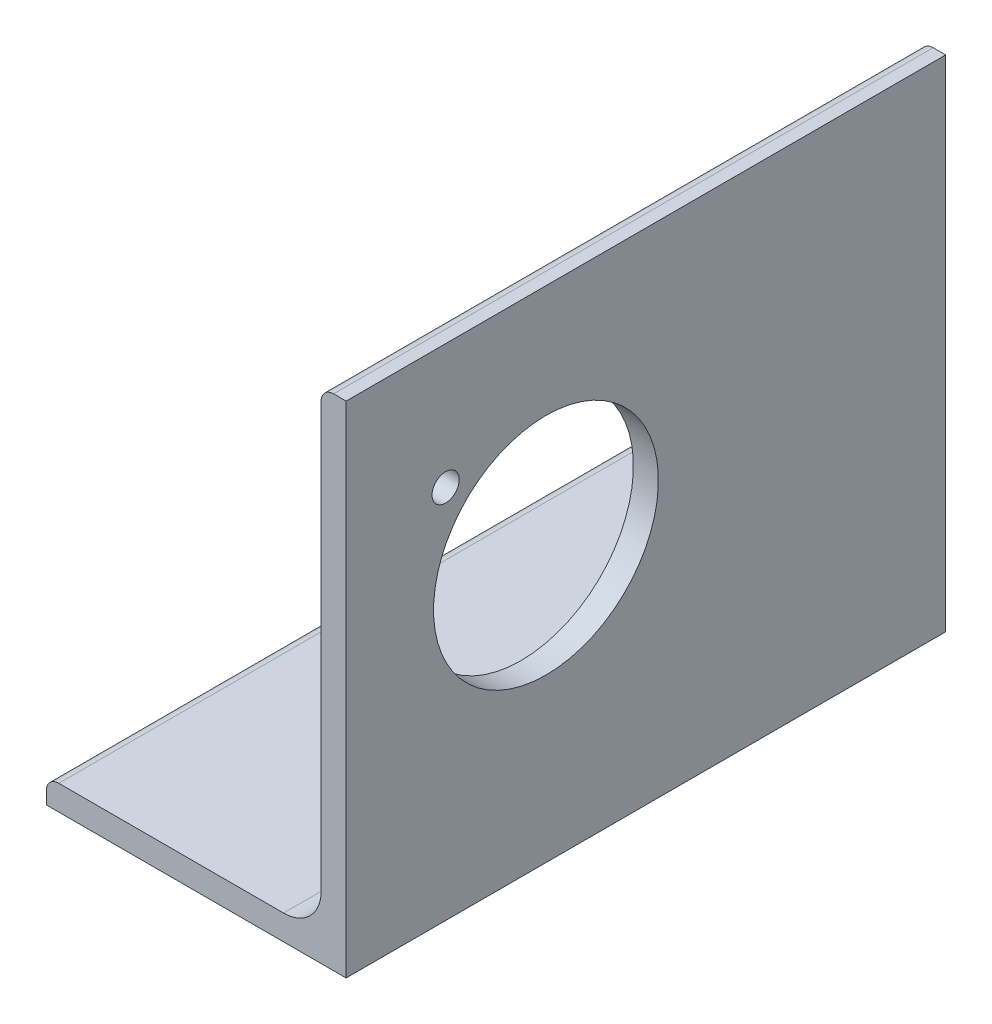
SolidWorks part; units mm, degrees
ref_plane "Front Plane" through (0, 0, 0) normal (0, 0, 1) x (1, 0, 0)
ref_plane "Top Plane" through (0, 0, 0) normal (0, 1, 0) x (1, 0, 0)
ref_plane "Right Plane" through (0, 0, 0) normal (1, 0, 0) x (0, 0, -1)
sketch "Sketch0" plane through (0, 0, 0) normal (0, 0, 1) x (1, 0, 0)
  line L0 (-19.05, -31.75) -> (19.05, -31.75)
  line L1 (19.05, -31.75) -> (19.05, 31.75)
  line L2 (19.05, 0) -> (0, 0) construction
  line L3 (0, 0) -> (0, -31.75) construction
  line L4 (15.875, -23.7998) -> (15.875, 31.75) construction
  line L5 (11.0998, -28.575) -> (-19.05, -28.575) construction
  arc A0 (15.875, -23.7998) -> (11.0998, -28.575) centre (11.0998, -23.7998) cw
  point P3 (14.4764, -27.1764)
  dimension "Inside Corner Radius" = 4.7752
  dimension "Outside Height" = 63.5
  dimension "Inside Height" = 60.325
  dimension "Inside Width" = 34.925
  dimension "Wall Thickness" = 3.175
  dimension "D1" = 3.175
  dimension "Outside Width" = 38.1
sketch "Sketch1" plane through (0, 0, 0) normal (1, 0, 0) x (0, 0, -1)
  line L0 (38.1, 0) -> (-38.1, 0)
  point P4 (0, 0)
  dimension "Length" = 76.2
sketch "Sketch2" plane through (0, 0, 0) normal (0, 0, 1) x (1, 0, 0)
  line L0 (-19.05, -31.75) -> (19.05, -31.75)
  line L1 (19.05, -31.75) -> (19.05, 31.75)
  line L2 (19.05, 31.75) -> (15.875, 31.75) construction
  line L3 (15.875, 30.1625) -> (15.875, -23.7998)
  line L4 (11.0998, -28.575) -> (-17.4625, -28.575)
  line L5 (-19.05, -31.75) -> (-19.05, -28.575) construction
  line L6 (17.4625, 31.75) -> (19.05, 31.75)
  line L7 (-19.05, -30.1625) -> (-19.05, -31.75)
  line L8 (19.05, 0) -> (0, 0) construction
  line L9 (0, 0) -> (0, -31.75) construction
  arc A0 (15.875, 30.1625) -> (17.4625, 31.75) centre (17.4625, 30.1625) cw
  arc A1 (-19.05, -30.1625) -> (-17.4625, -28.575) centre (-17.4625, -30.1625) cw
  arc A2 (15.875, -23.7998) -> (11.0998, -28.575) centre (11.0998, -23.7998) cw
  dimension "Inside Radius" = 4.7752
  dimension "Height" = 63.5
  dimension "Width" = 38.1
  dimension "Thickness" = 3.175
extrude "Boss-Extrude1" add sketch "Sketch2" along normal mid plane 76.2
sketch "Break Locations" plane through (0, 0, 0) normal (1, 0, 0) x (0, 0, -1)
  line L0 (26.67, 0) -> (-26.67, 0)
  line L1 (-38.1, -31.75) -> (-38.1, 31.75) construction
  line L2 (38.1, -31.75) -> (38.1, 31.75) construction
  point P0 (15.875, 0)
  point P1 (-15.875, 0)
  point P10 (0, 0)
  point P11 (-26.67, 0)
  point P13 (26.67, 0)
  dimension "D1" = 53.975
  dimension "D2" = 53.975
  dimension "D3" = 64.77
sketch "Sketch3" plane through (15.875, 0, 0) normal (-1, 0, 0) x (0, 0, 1)
  line L0 (12.7, 3.1798) -> (25.452, 15.9317) construction
  line L1 (12.7, 3.1798) -> (38.1, 3.1813) construction
  line L2 (38.1, 30.1625) -> (38.1, -23.7998) construction
  circle A0 centre (12.7, 3.1798) radius 14.2875
  circle A1 centre (25.452, 15.9317) radius 1.7272
  dimension "D1" = 25.4
extrude "Cut-Extrude1" cut sketch "Sketch3" against normal through all
sketch "Sketch9" plane through (0, -31.75, 0) normal (0, -1, 0) x (1, 0, 0)
  line L0 (19.05, -12.7) -> (0, -12.7) construction
  line L2 (0, -12.7) -> (0, 0) construction
  line L3 (0, -12.7) -> (0, -25.4) construction
  circle A0 centre (0, 0) radius 2.4892
  circle A1 centre (0, -25.4) radius 2.4892
  point P2 (0, 0)
  dimension "D1" = 19.05
  dimension "D2" = 25.4
  dimension "D3" = 25.4
extrude "Cut-Extrude2" cut sketch "Sketch9" against normal through all
equation "\"D1@Break Locations\" = .85 * \"Height@Sketch2\""
equation "\"D2@Break Locations\"=\"D1@Break Locations\""
equation "\"Thickness@Sketch2\"=\"wall thickness@sketch0\""
equation "\"Height@Sketch2\"=\"outside height@sketch0\""
equation "\"Width@Sketch2\"=\"outside width@sketch0\""
equation "\"Inside Radius@Sketch2\"=\"inside corner radius@sketch0\""
equation "\"Length@Boss-Extrude1\"=\"length@sketch1\""
equation "\"D3@Break Locations\"=\"D2@Break Locations\"*1.2"
equation "\"D1@Sketch0\"=\"Wall Thickness@Sketch0\""
